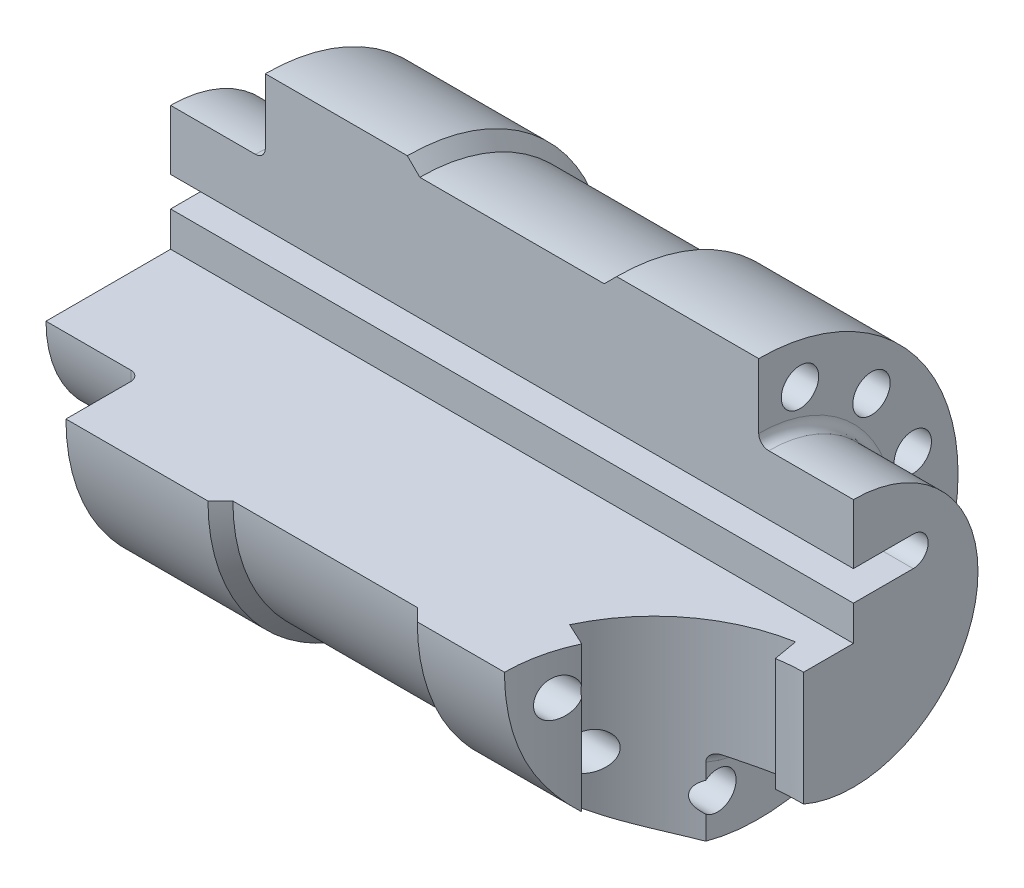
SolidWorks part; units mm, degrees
material "AISI 1020"
ref_plane "Plan de face" through (0, 0, 0) normal (0, 0, 1) x (1, 0, 0)
ref_plane "Plan de dessus" through (0, 0, 0) normal (0, 1, 0) x (1, 0, 0)
ref_plane "Plan de droite" through (0, 0, 0) normal (1, 0, 0) x (0, 0, -1)
sketch "Esquisse1" plane through (0, 0, 0) normal (0, 0, 1) x (1, 0, 0)
  line L0 (0, 0) -> (24.5663, 0)
  line L1 (24.5663, 0) -> (24.5663, 25)
  line L2 (24.5663, 25) -> (7.5663, 25)
  line L3 (5.5663, 27) -> (5.5663, 40)
  line L4 (5.5663, 40) -> (-22.9337, 40)
  line L5 (-22.9337, 40) -> (-25.4337, 37.5)
  line L6 (-25.4337, 37.5) -> (-62.4337, 37.5)
  line L7 (-62.4337, 37.5) -> (-64.9337, 40)
  line L8 (-64.9337, 40) -> (-93.4337, 40)
  line L9 (-93.4337, 40) -> (-93.4337, 27)
  line L10 (-95.4337, 25) -> (-112.4337, 25)
  line L11 (-112.4337, 25) -> (-112.4337, 0)
  line L12 (-112.4337, 0) -> (0, 0)
  line L13 (-130.7689, 0) -> (47.3428, 0) construction
  arc A0 (-95.4337, 25) -> (-93.4337, 27) centre (-95.4337, 27) ccw
  arc A1 (7.5663, 25) -> (5.5663, 27) centre (7.5663, 27) cw
  dimension "D11" = 2
  dimension "D13" = 2
  dimension "D1" = 25
  dimension "D2" = 40
  dimension "D3" = 19
  dimension "D4" = 19
  dimension "D5" = 28.5
  dimension "D6" = 28.5
  dimension "D7" = 2.5
  dimension "D8" = 2.5
  dimension "D9" = 225
  dimension "D10" = 225
  dimension "D12" = 25
  dimension "D14" = 137
revolve "Révolution1" add sketch "Esquisse1" angle 360 about L13
sketch "Esquisse2" plane through (-112.4337, 0, 0) normal (-1, 0, 0) x (0, 0, 1)
  line L0 (0, 0) -> (0, 7)
  line L1 (0, 0) -> (43.4498, 0)
  line L2 (0, 0) -> (0, 7)
  line L3 (0, 44.4974) -> (43.4498, 44.4974)
  line L4 (43.4498, 0) -> (43.4498, 44.4974)
  line L9 (0, 10) -> (-12, 10)
  line L10 (0, 10) -> (-12, 10) construction
  line L11 (0, 7) -> (-12, 7)
  line L12 (0, 13) -> (-12, 13)
  line L13 (0, 13) -> (0, 44.4974)
  arc A0 (0, 7) -> (0, 13) centre (0, 10) ccw
  arc A1 (-12, 13) -> (-12, 7) centre (-12, 10) ccw
  point P7 (-6, 10)
  dimension "D2" = 3
  dimension "D1" = 12
  dimension "D3" = 7
extrude "Enlèv. mat.-Extru.1" cut sketch "Esquisse2" against normal through all
sketch "Esquisse3" plane through (-93.4337, 0, 0) normal (-1, 0, 0) x (0, 0, 1)
  line L0 (0, 0) -> (-12.0134, 44.8348) construction
  line L1 (0, 13) -> (0, 25) construction
  line L2 (0, 0) -> (-8.2822, 30.9096) construction
  line L3 (0, 0) -> (-22.6274, 22.6274) construction
  circle A0 centre (0, 0) radius 32 construction
  circle A1 centre (-8.2822, 30.9096) radius 3.75
  circle A2 centre (-22.6274, 22.6274) radius 3.75
  circle A3 centre (-30.9096, 8.2822) radius 3.75
  circle A4 centre (-30.9096, -8.2822) radius 3.75
  circle A5 centre (-22.6274, -22.6274) radius 3.75
  circle A6 centre (-8.2822, -30.9096) radius 3.75
  circle A7 centre (8.2822, -30.9096) radius 3.75
  circle A8 centre (22.6274, -22.6274) radius 3.75
  circle A9 centre (30.9096, -8.2822) radius 3.75
  dimension "D1" = 64
  dimension "D2" = 7.5
  dimension "D3" = 15
  dimension "D5" = 30
  dimension "D4" = 9
extrude "Enlèv. mat.-Extru.2" cut sketch "Esquisse3" against normal through all
sketch "Esquisse4" plane through (0, 0, 0) normal (0, 1, 0) x (1, 0, 0)
  line L0 (24.5663, -25) -> (24.5663, -40) construction
  line L1 (5.5663, -40) -> (24.5663, -40) construction
  line L2 (24.5663, -40) -> (24.5663, -5)
  line L3 (24.5663, -40) -> (-10.4337, -40)
  line L4 (24.5663, -40) -> (-7.1545, -25.2084)
  line L5 (24.5663, -40) -> (18.4886, -5.5317)
  arc A0 (24.5663, -10) -> (-5.4337, -40) centre (24.5663, -40) ccw
  arc A1 (24.5663, -5) -> (-10.4337, -40) centre (24.5663, -40) ccw
  line M14 (5.5663, -40) -> (5.5663, -27)
  arc M15 (5.5663, -27) -> (7.5663, -25) centre (7.5663, -27) cw
  line M16 (7.5663, -25) -> (24.5663, -25)
  line M17 (24.5663, -25) -> (24.5663, 0)
  dimension "D1" = 70
  dimension "D2" = 60
  dimension "D3" = 10
  dimension "D4" = 25
extrude "Enlèv. mat.-Extru.3" cut sketch "Esquisse4" against normal through all contours L4 L5 M16 M15 M14 | L4 A0 L3 M14 | L5 A0 L4 M14 M15 M16 | L3 L4 M14 | L5 A1 L4 A0 | A0 L5 M17 M16 | L5 L2 M16
sketch "Esquisse5" plane through (-112.4337, 0, 0) normal (-1, 0, 0) x (0, 0, 1)
  line L0 (20.6155, -4) -> (-4, -4)
  line L1 (-4, -4) -> (-4, 3)
  line L2 (-4, 3) -> (-20.7846, 3)
  line L3 (0, 0) -> (0, 7) construction
  line L7 (0, 0) -> (25, 0) construction
  line L9 (0, 7) -> (-12, 7) construction
  arc A0 (-20.7846, 3) -> (20.6155, -4) centre (0, 0) ccw
  arc A4 (0, 25) -> (25, 0) centre (0, 0) ccw construction
  arc A5 (0, 25) -> (25, 0) centre (0, 0) ccw construction
  dimension "D3" = 4
  dimension "D1" = 4
  dimension "D2" = 4
  dimension "D5" = 4
extrude "Enlèv. mat.-Extru.4" cut sketch "Esquisse5" against normal blind 10
fillet "Congé1" radius 1 4 edges at (-102.4337, 3, -12.3923) (-102.4337, -0.5, -4) (-102.4337, -4, 8.3078) (-102.4337, -20.7061, -3.501)
equation "\"A\"= 137"
equation "\"B\"= 19"
equation "\"C\"= 28.5"
equation "\"D3@Esquisse1\"=\"B\""
equation "\"D4@Esquisse1\"=\"B\""
equation "\"D5@Esquisse1\"=\"C\""
equation "\"D6@Esquisse1\"=\"C\""
equation "\"D14@Esquisse1\"=\"A\""
